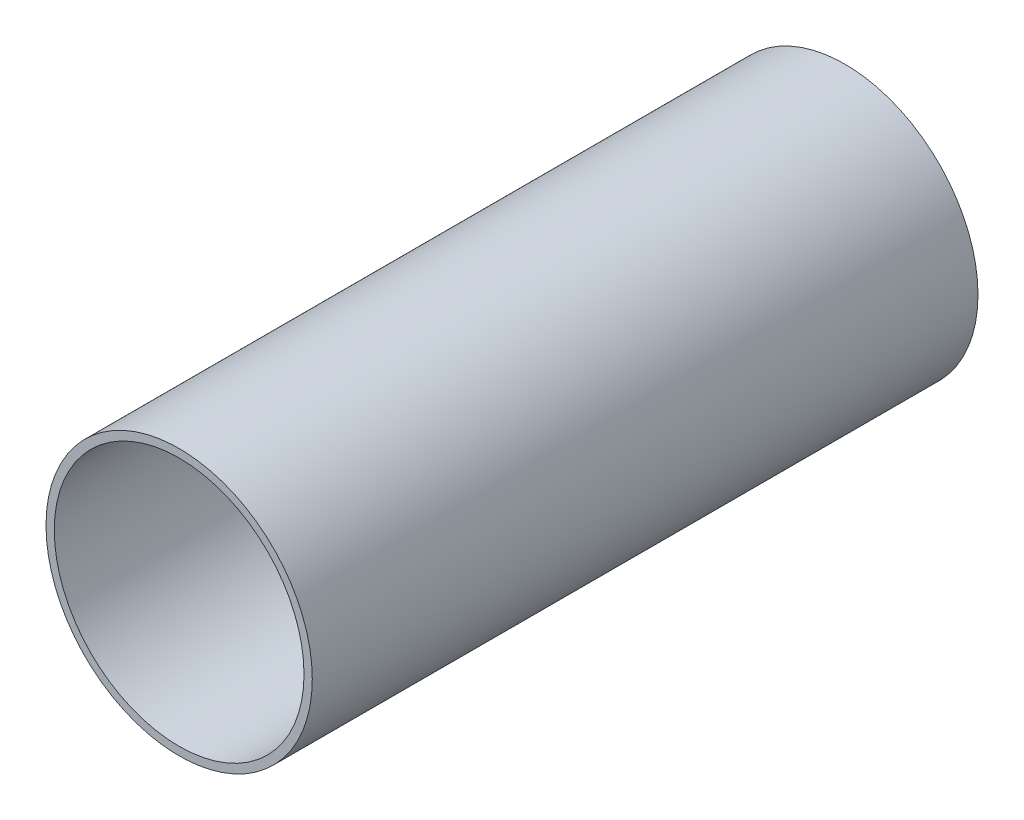
SolidWorks part; units mm, degrees
ref_plane "Front Plane" through (0, 0, 0) normal (0, 0, 1) x (1, 0, 0)
ref_plane "Top Plane" through (0, 0, 0) normal (0, 1, 0) x (1, 0, 0)
ref_plane "Right Plane" through (0, 0, 0) normal (1, 0, 0) x (0, 0, -1)
sketch "Sketch1" plane through (0, 0, 0) normal (0, 0, 1) x (1, 0, 0)
  circle A0 centre (0, 0) radius 50.8
  circle A1 centre (0, 0) radius 47.6458
  dimension "D1" = 101.6
  dimension "D2" = 95.2915
extrude "Boss-Extrude1" add sketch "Sketch1" along normal blind 254
